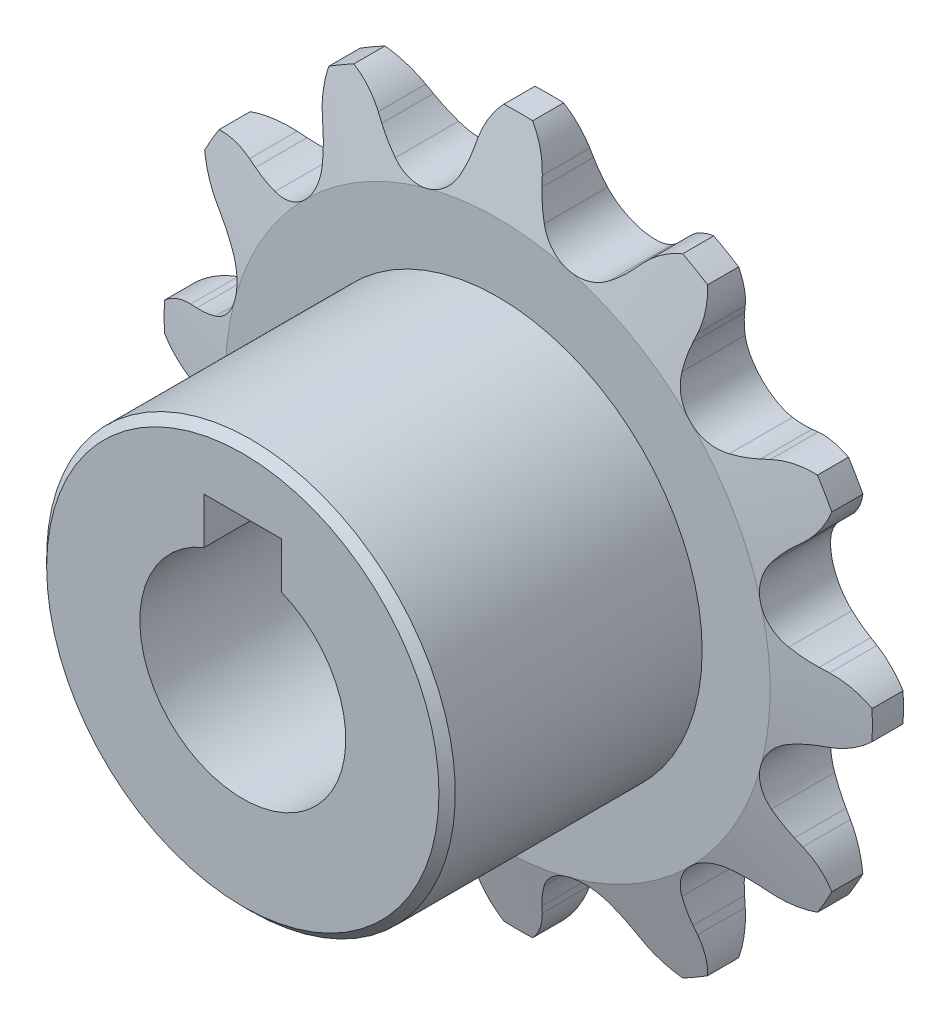
SolidWorks part; units mm, degrees
material "1023 Carbon Steel Sheet (SS)"
ref_plane "Front Plane" through (0, 0, 0) normal (0, 0, 1) x (1, 0, 0)
ref_plane "Top Plane" through (0, 0, 0) normal (0, 1, 0) x (1, 0, 0)
ref_plane "Right Plane" through (0, 0, 0) normal (1, 0, 0) x (0, 0, -1)
sketch "Sketch0" plane through (0, 0, 0) normal (0, 0, 1) x (1, 0, 0)
  line L0 (3.175, -11.8493) -> (0, 0) construction
  line L1 (0, 0) -> (8.6743, -8.6743) construction
  line L2 (0, 0) -> (-3.175, -11.8493) construction
  line L3 (3.175, -11.8493) -> (8.6743, -8.6743) construction
  line L4 (3.175, -11.8493) -> (-3.175, -11.8493) construction
  line L5 (5.1176, -11.3719) -> (4.9011, -11.1286)
  line L6 (3.175, -11.8493) -> (0, -12.7) construction
  line L7 (1.2539, -12.4071) -> (1.3198, -12.0882)
  line L8 (0, -11.8493) -> (0, -13.7543) construction
  line L9 (4.1486, -10.4589) -> (1.6598, -14.0131) construction
  line L10 (0, 0) -> (0, -11.8493) construction
  line L11 (4.9011, -11.1286) -> (1.6598, -14.0131) construction
  line L12 (0, -13.7543) -> (0, -14.1976) construction
  line L13 (7.1785, -9.5379) -> (5.1176, -11.3719) construction
  circle A0 centre (0, 0) radius 13.7543 construction
  circle A1 centre (0, 0) radius 12.2673 construction
  arc A2 (-1.7824, -14.5876) -> (8.8374, -11.7421) centre (0, 0) ccw
  circle A3 centre (0, 0) radius 14.1976 construction
  circle A4 centre (3.175, -11.8493) radius 1.651 construction
  arc A7 (4.1486, -10.4589) -> (1.6367, -11.1319) centre (3.175, -11.8493) ccw
  circle A8 centre (3.175, -11.8493) radius 1.6974 construction
  arc A9 (5.1176, -11.3719) -> (8.8374, -11.7421) centre (7.1785, -9.5379) ccw
  arc A10 (4.9011, -11.1286) -> (4.1486, -10.4589) centre (1.6598, -14.0131) ccw
  arc A11 (1.2539, -12.4071) -> (-1.7824, -14.5876) centre (-1.4478, -11.8493) cw
  arc A12 (1.3198, -12.0882) -> (1.6367, -11.1319) centre (5.5691, -12.9656) cw
  dimension "D1" = 1.6974
  dimension "R" = 1.6974
sketch "Sketch1" plane through (0, 0, 0) normal (1, 0, 0) x (0, 0, -1)
  line L0 (1.397, 0) -> (-1.397, 0)
  line L1 (-1.397, 0) -> (-1.397, 10.5793)
  line L2 (-1.397, 10.5793) -> (-0.6033, 13.7543)
  line L3 (-0.6033, 13.7543) -> (0.6033, 13.7543)
  line L4 (0.6033, 13.7543) -> (1.397, 10.5793)
  line L5 (1.397, 10.5793) -> (1.397, 0)
  line L7 (0, 13.7543) -> (0, 0) construction
  line L8 (-1.397, 10.5793) -> (1.397, 10.5793) construction
  line L9 (0, 13.7543) -> (0, -13.7543) construction
  line L10 (-1.397, 10.5793) -> (-1.397, 13.7543) construction
  line L11 (-1.397, 13.7543) -> (-0.6033, 13.7543) construction
  line L12 (0.6033, 13.7543) -> (1.397, 13.7543) construction
  line L13 (1.397, 13.7543) -> (1.397, 10.5793) construction
  line L14 (0, 0) -> (-6.4008, 0) construction
  line L22 (1.397, 0) -> (-11.303, 0) construction
  line L24 (-1.397, 0) -> (-1.397, 8.2933) construction
revolve "Revolve1" add sketch "Sketch1" angle 360 mid plane about L0
extrude "Cut-Extrude1" cut sketch "Sketch0" against normal through all and the other way through all
pattern_circular "CirPattern1" count 12 over 360 about axis through (0, 0, 0) along (0, 0, 1) of "Cut-Extrude1"
sketch "Sketch2" plane through (0, 0, 0) normal (0, 0, 1) x (1, 0, 0)
  circle A0 centre (0, 0) radius 3.175 construction
  circle A1 centre (0, 0) radius 7.9375
  circle A2 centre (0, 0) radius 13.716 construction
  dimension "Bore" = 6.35
  dimension "Hub Dia." = 15.875
  dimension "OD" = 27.432
extrude "Boss-Extrude1" add sketch "Sketch2" along normal up to vertex (11.303 mm away) from surface at 1.397 starting at face at (0, 0, 1.397)
sketch "Sketch3" plane through (0, 0, 0) normal (0, 0, 1) x (1, 0, 0)
  circle A0 centre (0, 0) radius 3.175 construction
  circle A1 centre (0, 0) radius 3.175
extrude "Cut-Extrude2" cut sketch "Sketch3" along normal through all and the other way through all
sketch "Sketch4" plane through (0, 0, 0) normal (1, 0, 0) x (0, 0, -1)
  line L0 (-11.303, 7.9375) -> (-11.303, 7.62)
  line L1 (-1.397, 13.7543) -> (-3.4925, 13.7543)
  line L2 (-1.397, 13.7543) -> (-1.397, 8.2933)
  line L3 (-1.397, 8.2933) -> (-3.4925, 8.2933)
  line L4 (-3.4925, 13.7543) -> (-3.4925, 8.2933)
  line L9 (-11.303, 7.62) -> (-10.9855, 7.9375)
  line L10 (-10.9855, 7.9375) -> (-11.303, 7.9375)
  dimension "C" = 0.3175
  dimension "D3" = 2.0955
revolve "Cut-Revolve1" cut sketch "Sketch4" angle 360 mid plane about L22
sketch "Sketch5" plane through (0, 0, 11.303) normal (0, 0, 1) x (1, 0, 0)
  line L1 (-1.5, 2.5) -> (1.5, 2.5)
  line L2 (-1.5, 2.5) -> (-1.5, 5.5)
  line L3 (-1.5, 5.5) -> (1.5, 5.5)
  line L4 (1.5, 2.5) -> (1.5, 5.5)
  line L5 (-1.5, 2.5) -> (1.5, 5.5) construction
  line L6 (-1.5, 5.5) -> (1.5, 2.5) construction
  circle A0 centre (0, 0) radius 4
  point P3 (0, 4)
  circle M6 centre (0, 0) radius 3.175
  dimension "D1" = 8
  dimension "D2" = 3
extrude "Cut-Extrude4" cut sketch "Sketch5" against normal through all contours L2 A0 L4 M6 | A0 L4 L3 L2 | L4 A0 L2 M6 | L1 L4 L2 M6
equation "\"360/N@Sketch0\" = 360/\"Teeth@CirPattern1\""
equation "\"Ds@Sketch0\" = 1.005 * \"Dr@Sketch0\" + 0.003"
equation "\"R@Sketch0\" = 1/2 * \"Ds@Sketch0\""
equation "\"A@Sketch0\" = 35 +  ( 60 / \"Teeth@CirPattern1\" ) "
equation "\"B@Sketch0\" = 18 -  ( 56 / \"Teeth@CirPattern1\" )"
equation "\"ac@Sketch0\" = 0.8 * \"Dr@Sketch0\""
equation "\"ab@Sketch0\" = 1.4 * \"Dr@Sketch0\""
equation "\"J@Sketch0\" = 0.3 * \"Pitch@Sketch0\""
equation "\"h@Sketch1\" = \"Pitch@Sketch0\" / 2"
equation "\"g@Sketch1\" = \"h@Sketch1\" / 4"
equation "\"MHD@Sketch1\" = \"Pitch@Sketch0\" * ( cotan ( 180 / \"Teeth@CirPattern1\" ) - 1 ) - 0.030"
equation "\"D3@Sketch4\" = \"t@Sketch1\" * 3 / 4"
